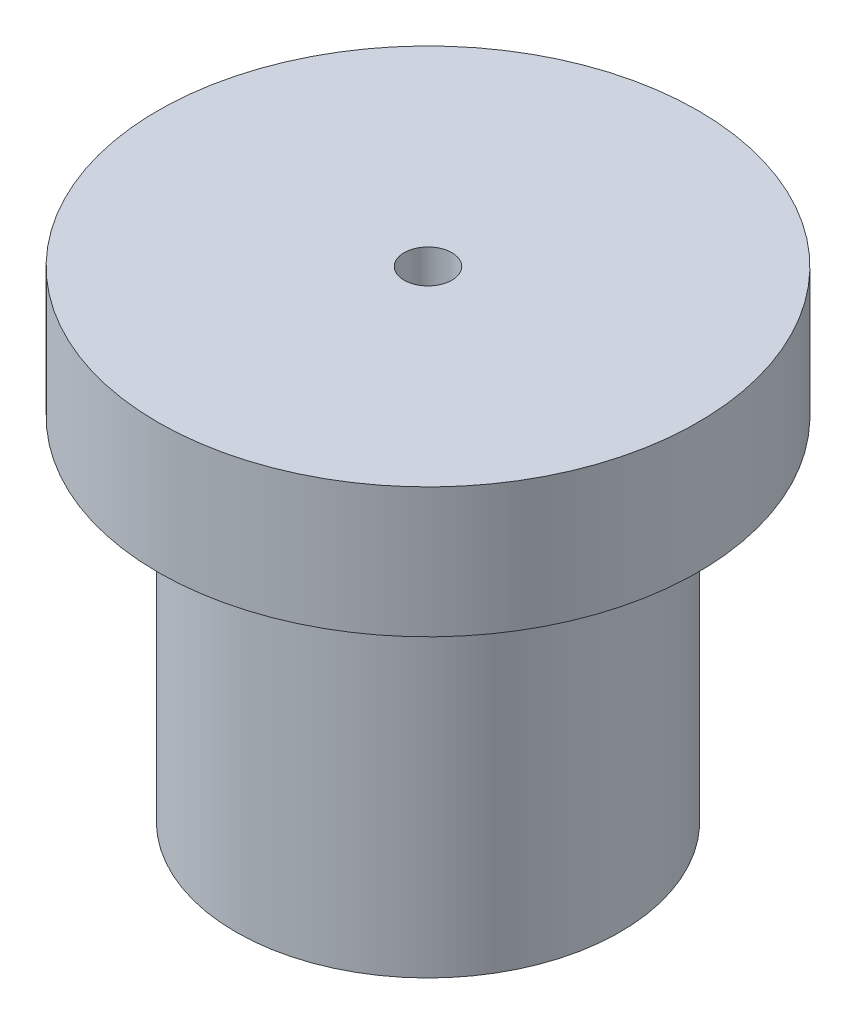
SolidWorks part; units mm, degrees
ref_plane "Front Plane" through (0, 0, 0) normal (0, 0, 1) x (1, 0, 0)
ref_plane "Top Plane" through (0, 0, 0) normal (0, 1, 0) x (1, 0, 0)
ref_plane "Right Plane" through (0, 0, 0) normal (1, 0, 0) x (0, 0, -1)
sketch "Sketch1" plane through (0, 0, 0) normal (0, 1, 0) x (1, 0, 0)
  circle A0 centre (0, 0) radius 9.398
  circle A1 centre (0, 0) radius 1.1684
  dimension "D1" = 18.796
  dimension "D2" = 2.3368
extrude "Boss-Extrude1" add sketch "Sketch1" along normal blind 17.145
sketch "Sketch2" plane through (0, 17.145, 0) normal (0, 1, 0) x (1, 0, 0)
  circle A0 centre (0, 0) radius 13.208
  circle A1 centre (0, 0) radius 9.398 construction
  circle A2 centre (0, 0) radius 1.1684
  circle A3 centre (0, 0) radius 1.1684 construction
  dimension "D1" = 3.81
extrude "Boss-Extrude2" add sketch "Sketch2" along normal blind 6.35
